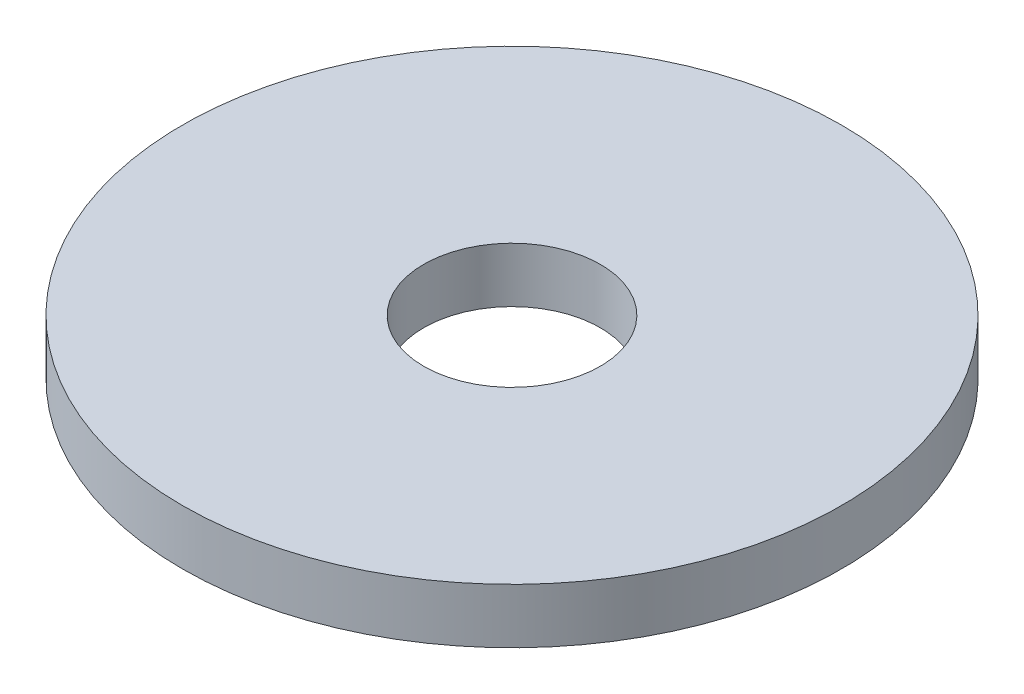
SolidWorks part; units mm, degrees
material "6061-T6 (SS)"
ref_plane "Front Plane" through (0, 0, 0) normal (0, 0, 1) x (1, 0, 0)
ref_plane "Top Plane" through (0, 0, 0) normal (0, 1, 0) x (1, 0, 0)
ref_plane "Right Plane" through (0, 0, 0) normal (1, 0, 0) x (0, 0, -1)
sketch "Sketch1" plane through (0, 0, 0) normal (0, 1, 0) x (1, 0, 0)
  circle A0 centre (0, 0) radius 2.5527
  circle A1 centre (0, 0) radius 9.525
  dimension "D1" = 5.1054
  dimension "D2" = 19.05
extrude "Boss-Extrude1" add sketch "Sketch1" along normal blind 1.5875
